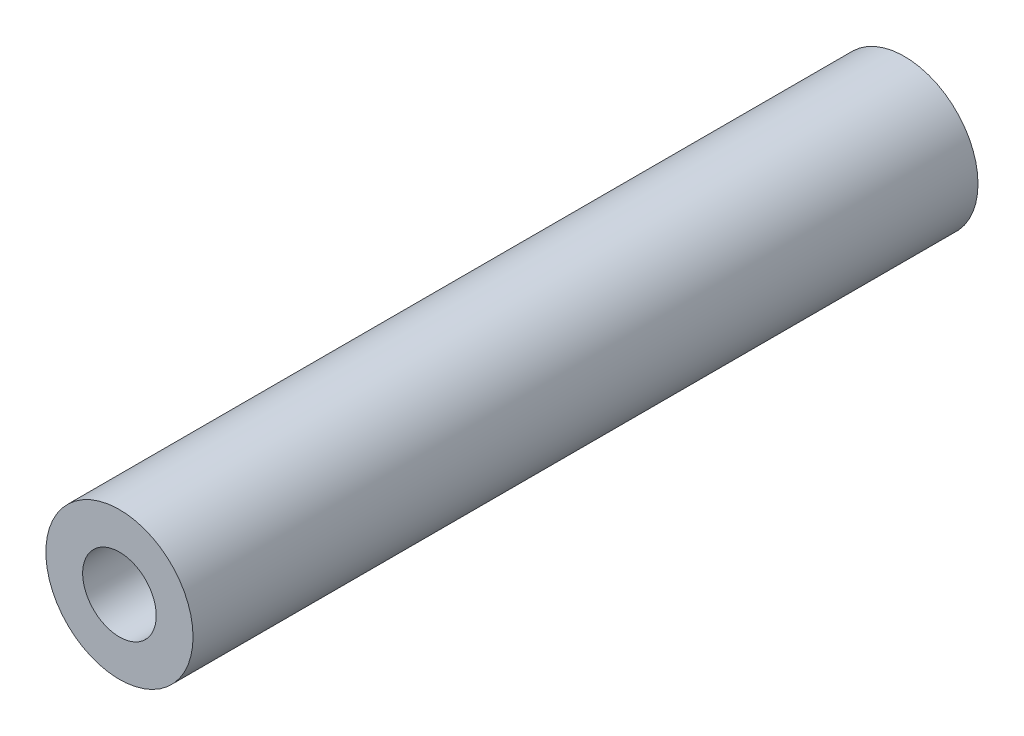
SolidWorks part; units mm, degrees
ref_plane "正面" through (0, 0, 0) normal (0, 0, 1) x (1, 0, 0)
ref_plane "平面" through (0, 0, 0) normal (0, 1, 0) x (1, 0, 0)
ref_plane "右側面" through (0, 0, 0) normal (1, 0, 0) x (0, 0, -1)
sketch "ｽｹｯﾁ1" plane through (0, 0, 0) normal (0, 0, 1) x (1, 0, 0)
  circle A0 centre (0, 0) radius 3
  circle A1 centre (0, 0) radius 1.5
  dimension "D1" = 6
  dimension "D2" = 3
extrude "ﾎﾞｽ - 押し出し1" add sketch "ｽｹｯﾁ1" along normal blind 32
